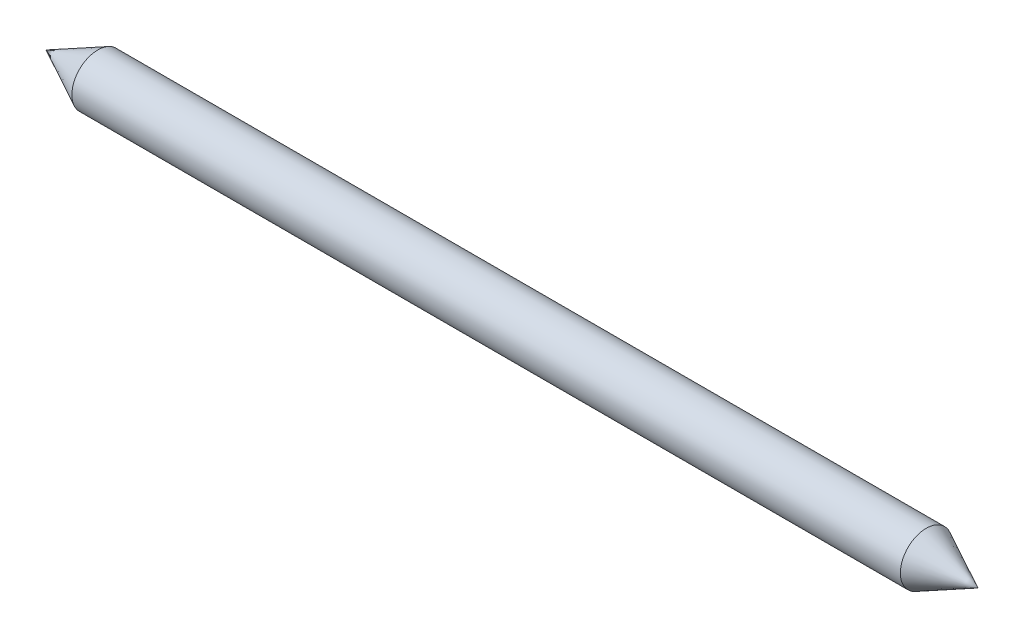
SolidWorks part; units mm, degrees
ref_plane "Front Plane" through (0, 0, 0) normal (0, 0, 1) x (1, 0, 0)
ref_plane "Top Plane" through (0, 0, 0) normal (0, 1, 0) x (1, 0, 0)
ref_plane "Right Plane" through (0, 0, 0) normal (1, 0, 0) x (0, 0, -1)
sketch "Sketch1" plane through (0, 0, 0) normal (0, 1, 0) x (1, 0, 0)
  line L0 (-228.6, 0) -> (228.6, 0)
  line L1 (228.6, 0) -> (203.2, 12.7)
  line L2 (203.2, 12.7) -> (-203.2, 12.7)
  line L3 (-203.2, 12.7) -> (-228.6, 0)
  point P4 (-224.5171, 45.5645)
  point P5 (0, 0)
  dimension "D1" = 457.2
  dimension "D2" = 12.7
  dimension "D3" = 25.4
revolve "Revolve1" add sketch "Sketch1" angle 360 about L0
